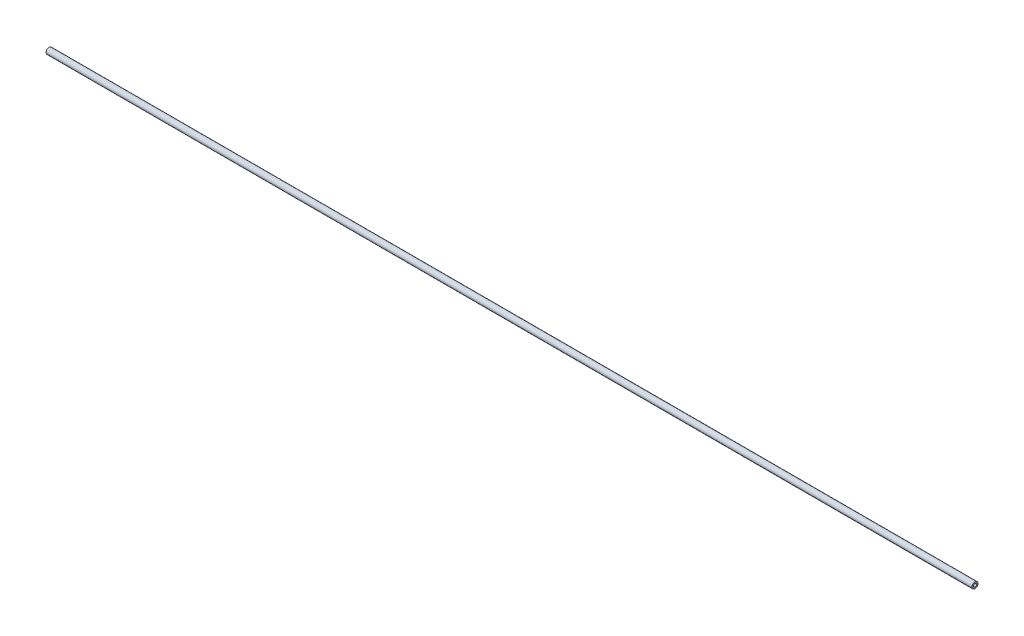
SolidWorks part; units mm, degrees
ref_plane "Front" through (0, 0, 0) normal (0, 0, 1) x (1, 0, 0)
ref_plane "Top" through (0, 0, 0) normal (0, 1, 0) x (1, 0, 0)
ref_plane "Right" through (0, 0, 0) normal (1, 0, 0) x (0, 0, -1)
sketch "Sketch1" plane through (0, 0, 0) normal (1, 0, 0) x (0, 0, -1)
  circle A0 centre (0, 0) radius 1
  circle A1 centre (0, 0) radius 0.5
  point P4 (1, 0)
  point P5 (0.5, 0)
  dimension "OD" = 2
  dimension "ID" = 1
  dimension "Wall" = 0.5
extrude "Extrude1" add sketch "Sketch1" along normal mid plane 304.8
